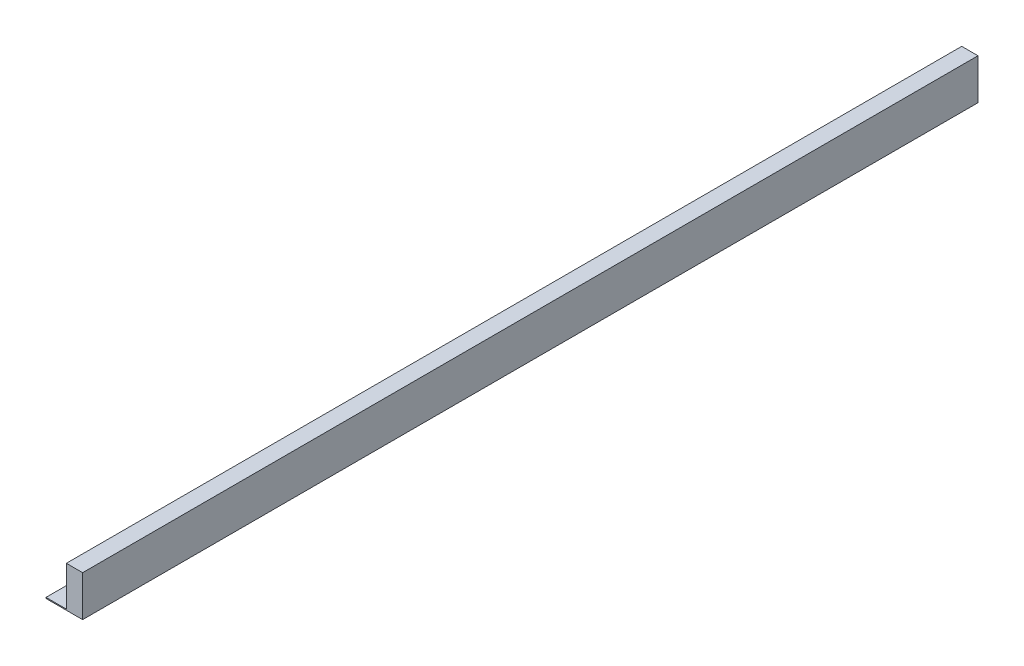
SolidWorks part; units mm, degrees
material "Galvanized Steel"
ref_plane "Front Plane" through (0, 0, 0) normal (0, 0, 1) x (1, 0, 0)
ref_plane "Top Plane" through (0, 0, 0) normal (0, 1, 0) x (1, 0, 0)
ref_plane "Right Plane" through (0, 0, 0) normal (1, 0, 0) x (0, 0, -1)
sketch "Sketch1" plane through (0, 0, 0) normal (0, 0, 1) x (1, 0, 0)
  line L1 (-6.35, -15.24) -> (6.35, -15.24)
  line L2 (-6.35, -15.24) -> (-6.35, 15.24)
  line L3 (-6.35, 15.24) -> (6.35, 15.24)
  line L4 (6.35, -15.24) -> (6.35, 15.24)
  line L5 (-6.35, -15.24) -> (6.35, 15.24) construction
  line L6 (-6.35, 15.24) -> (6.35, -15.24) construction
  point P0 (0, 0)
  dimension "D1" = 30.48
  dimension "D2" = 12.7
extrude "Boss-Extrude1" add sketch "Sketch1" along normal blind 558.8
sketch "Sketch2" plane through (0, 0, 558.8) normal (0, 0, 1) x (1, 0, 0)
  line L0 (-6.35, 15.24) -> (-6.35, -15.24) construction
  line L1 (-6.35, 12.7) -> (3.81, 12.7)
  line L2 (-6.35, 12.7) -> (-6.35, -12.7)
  line L3 (-6.35, -12.7) -> (3.81, -12.7)
  line L4 (3.81, 12.7) -> (3.81, -12.7)
  line L5 (6.35, 15.24) -> (-6.35, 15.24) construction
  line L6 (6.35, -15.24) -> (6.35, 15.24) construction
  line L7 (-6.35, -15.24) -> (6.35, -15.24) construction
  dimension "D1" = 2.54
  dimension "D2" = 2.54
  dimension "D3" = 2.54
extrude "Cut-Extrude1" cut sketch "Sketch2" against normal through all flip side to cut
sketch "Sketch3" plane through (0, 0, 0) normal (0, 0, 1) x (1, 0, 0)
  line L1 (-6.35, -12.7) -> (-19.05, -12.7)
  line L2 (-6.35, -12.7) -> (-6.35, -12.065)
  line L3 (-6.35, -12.065) -> (-19.05, -12.065)
  line L4 (-19.05, -12.7) -> (-19.05, -12.065)
  dimension "D1" = 19.05
  dimension "D2" = 0.635
extrude "Boss-Extrude2" add sketch "Sketch3" along normal up to surface (558.8 mm away) up to face at (-1.27, 0, 558.8)
